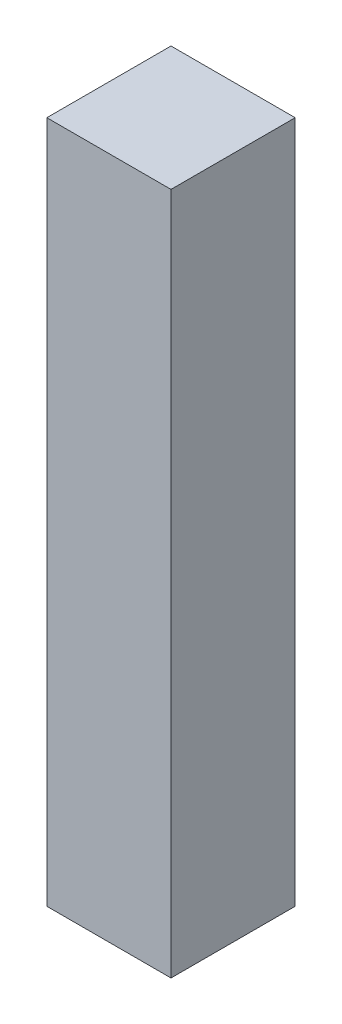
SolidWorks part; units mm, degrees
material "Balsa"
ref_plane "Alzado" through (0, 0, 0) normal (0, 0, 1) x (1, 0, 0)
ref_plane "Planta" through (0, 0, 0) normal (0, 1, 0) x (1, 0, 0)
ref_plane "Vista lateral" through (0, 0, 0) normal (1, 0, 0) x (0, 0, -1)
sketch "Croquis1" plane through (0, 0, 0) normal (0, 1, 0) x (1, 0, 0)
  line L1 (-2.5, -2.5) -> (2.5, -2.5)
  line L2 (-2.5, -2.5) -> (-2.5, 2.5)
  line L3 (-2.5, 2.5) -> (2.5, 2.5)
  line L4 (2.5, -2.5) -> (2.5, 2.5)
  line L5 (-2.5, -2.5) -> (2.5, 2.5) construction
  line L6 (-2.5, 2.5) -> (2.5, -2.5) construction
  point P0 (0, 0)
  dimension "D1" = 5
  dimension "D2" = 5
extrude "Saliente-Extruir1" add sketch "Croquis1" along normal mid plane 27.5
